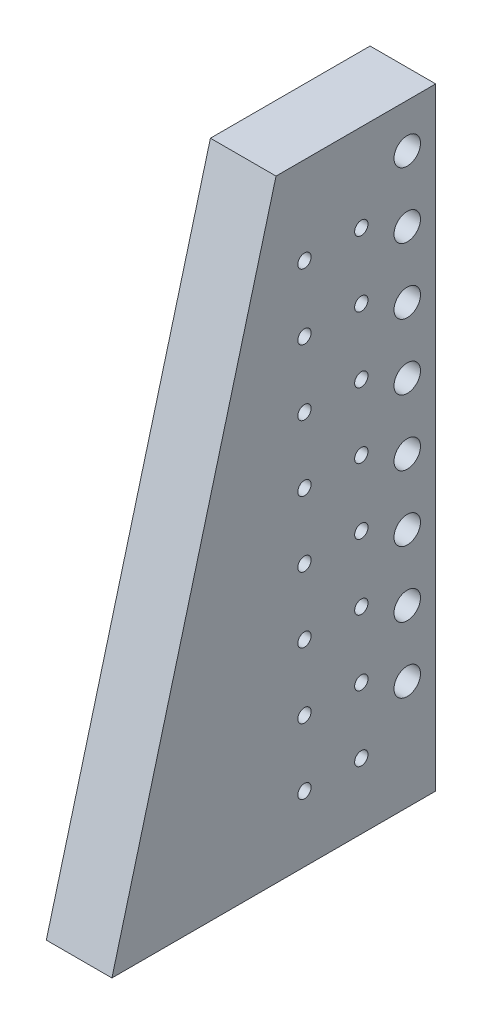
SolidWorks part; units mm, degrees
ref_plane "Front Plane" through (0, 0, 0) normal (0, 0, 1) x (1, 0, 0)
ref_plane "Top Plane" through (0, 0, 0) normal (0, 1, 0) x (1, 0, 0)
ref_plane "Right Plane" through (0, 0, 0) normal (1, 0, 0) x (0, 0, -1)
sketch "Sketch2" plane through (0, 0, 0) normal (1, 0, 0) x (0, 0, -1)
  line L0 (11.4872, 68.2051) -> (11.4872, -71.7949) construction
  line L1 (-56.0257, -71.7949) -> (17.9872, -71.7949)
  line L3 (-18.5128, 68.2051) -> (17.9872, 68.2051)
  line L4 (17.9872, -71.7949) -> (17.9872, 68.2051)
  line L7 (-56.0257, -71.7949) -> (-18.5128, 68.2051)
  circle A0 centre (11.4872, 58.2051) radius 3.025
  circle A1 centre (11.4872, 43.2051) radius 3.025
  circle A2 centre (11.4872, 28.2051) radius 3.025
  circle A3 centre (11.4872, 13.2051) radius 3.025
  circle A4 centre (11.4872, -1.7949) radius 3.025
  circle A5 centre (11.4872, -16.7949) radius 3.025
  circle A6 centre (11.4872, -31.7949) radius 3.025
  circle A7 centre (11.4872, -46.7949) radius 3.025
  circle A9 centre (0.9872, 48.2051) radius 1.525
  circle A10 centre (-12.0128, 48.2051) radius 1.525
  circle A11 centre (0.9872, 33.2051) radius 1.525
  circle A12 centre (-12.0128, 33.2051) radius 1.525
  circle A13 centre (0.9872, 18.2051) radius 1.525
  circle A14 centre (-12.0128, 18.2051) radius 1.525
  circle A15 centre (0.9872, 3.2051) radius 1.525
  circle A16 centre (-12.0128, 3.2051) radius 1.525
  circle A17 centre (0.9872, -11.7949) radius 1.525
  circle A18 centre (-12.0128, -11.7949) radius 1.525
  circle A19 centre (0.9872, -26.7949) radius 1.525
  circle A20 centre (-12.0128, -26.7949) radius 1.525
  circle A21 centre (0.9872, -41.7949) radius 1.525
  circle A22 centre (-12.0128, -41.7949) radius 1.525
  circle A23 centre (0.9872, -56.7949) radius 1.525
  circle A24 centre (-12.0128, -56.7949) radius 1.525
  point P0 (0, 0)
  dimension "D3" = 10
  dimension "D8" = 13
  dimension "D6" = 3.05
  dimension "D1" = 140
  dimension "D2" = 30
  dimension "D5" = 6.5
  dimension "D7" = 15
  dimension "D9" = 75
  dimension "D10" = 10
  dimension "D11" = 10.5
  dimension "D4" = 8
  dimension "D12" = 8
extrude "Boss-Extrude2" add sketch "Sketch2" along normal blind 15
